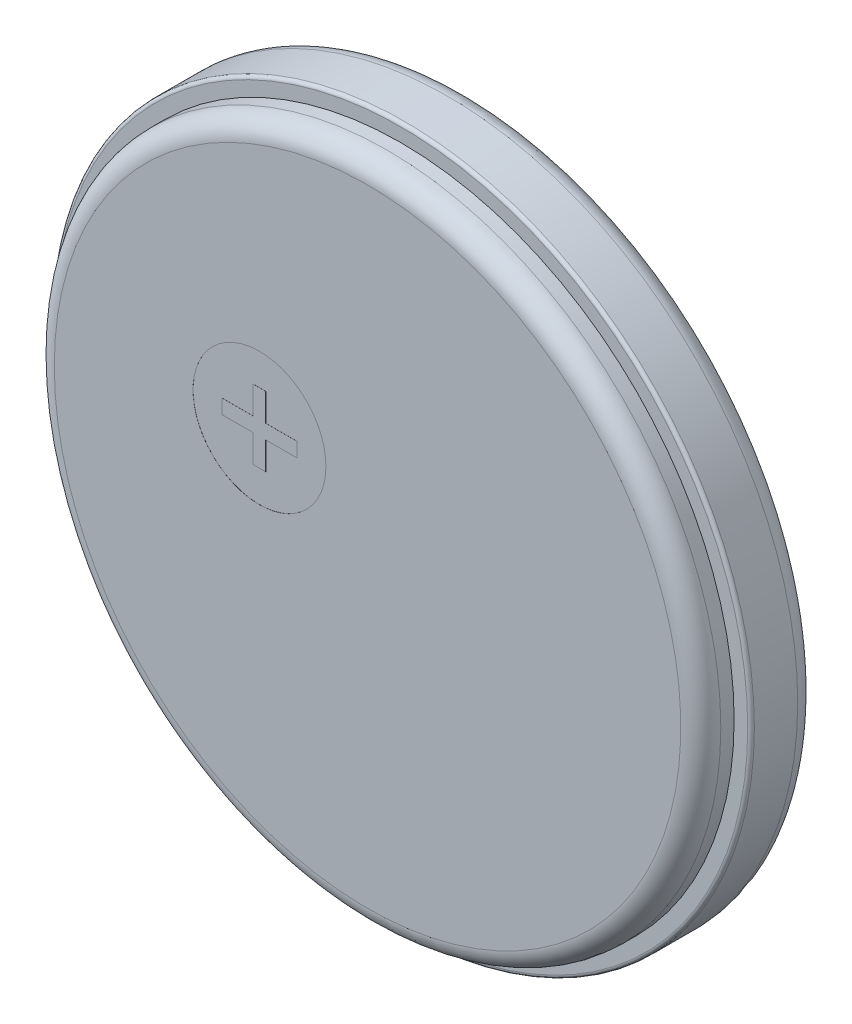
SolidWorks part; units mm, degrees
ref_plane "Front Plane" through (0, 0, 0) normal (0, 0, 1) x (1, 0, 0)
ref_plane "Top Plane" through (0, 0, 0) normal (0, 1, 0) x (1, 0, 0)
ref_plane "Right Plane" through (0, 0, 0) normal (1, 0, 0) x (0, 0, -1)
sketch "Sketch2" plane through (0, 0, 10.668) normal (0, 0, -1) x (-1, 0, 0)
  circle A0 centre (0, 31.75) radius 5
  dimension "D1" = 10
extrude "Boss-Extrude1" add sketch "Sketch2" along normal blind 0.5
fillet "Fillet1" radius 0.3 1 edges at (-5, 31.75, 10.668)
sketch "Sketch3" plane through (0, 0, 10.168) normal (0, 0, -1) x (-1, 0, 0)
  circle A2 centre (0, 31.75) radius 5.254
  circle A3 centre (0, 31.75) radius 5.254
  dimension "D1" = 0.254
extrude "Boss-Extrude2" add sketch "Sketch3" along normal blind 1
fillet "Fillet2" radius 0.3 1 edges at (-5.254, 31.75, 9.168)
fillet "Fillet3" radius 0.05 1 edges at (-5.254, 31.75, 10.168)
sketch "Sketch4" plane through (0, 0, 9.168) normal (0, 0, -1) x (-1, 0, 0)
  line L0 (-2.6501, 29.9289) -> (3.0044, 29.9289) construction
  line L1 (1.1417, 31.9299) -> (0.581, 33.5569)
  line L2 (0.581, 33.5569) -> (0.7228, 33.6419)
  line L3 (0.7228, 33.6419) -> (1.6489, 32.1001)
  line L4 (0.8246, 33.712) -> (1.7515, 32.1672)
  line L5 (0.8246, 33.712) -> (0.9402, 33.7813)
  line L6 (0.9402, 33.7813) -> (2.1566, 32.6492)
  arc A0 (1.6489, 32.1001) -> (1.7515, 32.1672) centre (0.992, 33.2168) ccw
  circle A1 centre (0.581, 33.947) radius 0.2042
  arc A3 (2.1566, 32.6492) -> (1.1417, 31.9299) centre (0.992, 33.2168) ccw
  text T0 "Lithium Ion" font "Impact" height in points 3
extrude "Cut-Extrude1" cut sketch "Sketch4" against normal blind 0.001
sketch "Sketch5" plane through (0, 0, 9.168) normal (0, 0, -1) x (-1, 0, 0)
  text T0 "Veltel" font "@Adobe Fan Heiti Std B" height in points 2
extrude "Cut-Extrude2" cut sketch "Sketch5" against normal blind 0.001
sketch "Sketch6" plane through (0, 0, 9.168) normal (0, 0, -1) x (-1, 0, 0)
  text T0 "CR5505" font "Century Gothic" height in points 2
extrude "Cut-Extrude3" cut sketch "Sketch6" against normal blind 0.001
sketch "Sketch7" plane through (0, 0, 9.168) normal (0, 0, -1) x (-1, 0, 0)
  line L1 (-1.3038, 33.2168) -> (-2.5226, 33.2168)
  line L2 (-1.3038, 33.2168) -> (-1.3038, 33.4152)
  line L3 (-1.3038, 33.4152) -> (-2.5226, 33.4152)
  line L4 (-2.5226, 33.2168) -> (-2.5226, 33.4152)
  line L5 (-1.3038, 33.2168) -> (-2.5226, 33.4152) construction
  line L6 (-1.3038, 33.4152) -> (-2.5226, 33.2168) construction
  circle A0 centre (-1.9132, 33.316) radius 0.8691
  point P0 (-1.9132, 33.316)
extrude "Cut-Extrude4" cut sketch "Sketch7" against normal blind 0.001
sketch "Sketch8" plane through (0, 0, 10.668) normal (0, 0, 1) x (1, 0, 0)
  line L0 (-1.7148, 32.5891) -> (-2.1834, 32.5891)
  line L1 (-1.7148, 31.9585) -> (-1.5276, 31.9585)
  line L2 (-1.7148, 32.5891) -> (-1.7148, 33.0042)
  line L3 (-1.7148, 33.0042) -> (-1.5276, 33.0042)
  line L4 (-1.5276, 31.9585) -> (-1.5276, 32.3736)
  line L5 (-1.7148, 31.9585) -> (-1.5276, 33.0042) construction
  line L6 (-1.7148, 33.0042) -> (-1.5276, 31.9585) construction
  line L7 (-1.059, 32.3736) -> (-1.5276, 32.3736)
  line L8 (-1.059, 32.3736) -> (-1.059, 32.5891)
  line L9 (-1.059, 32.5891) -> (-1.5276, 32.5891)
  line L10 (-2.1834, 32.3736) -> (-2.1834, 32.5891)
  line L11 (-1.059, 32.3736) -> (-2.1834, 32.5891) construction
  line L12 (-1.059, 32.5891) -> (-2.1834, 32.3736) construction
  line L13 (-1.7148, 31.9585) -> (-1.7148, 32.3736)
  line L14 (-1.5276, 32.5891) -> (-1.5276, 33.0042)
  line L16 (-1.7148, 32.3736) -> (-2.1834, 32.3736)
  circle A0 centre (-1.6212, 32.4814) radius 0.9969
  point P0 (-1.6212, 32.4814)
  point P5 (-1.6212, 32.4814)
extrude "Cut-Extrude5" cut sketch "Sketch8" against normal blind 0.001
